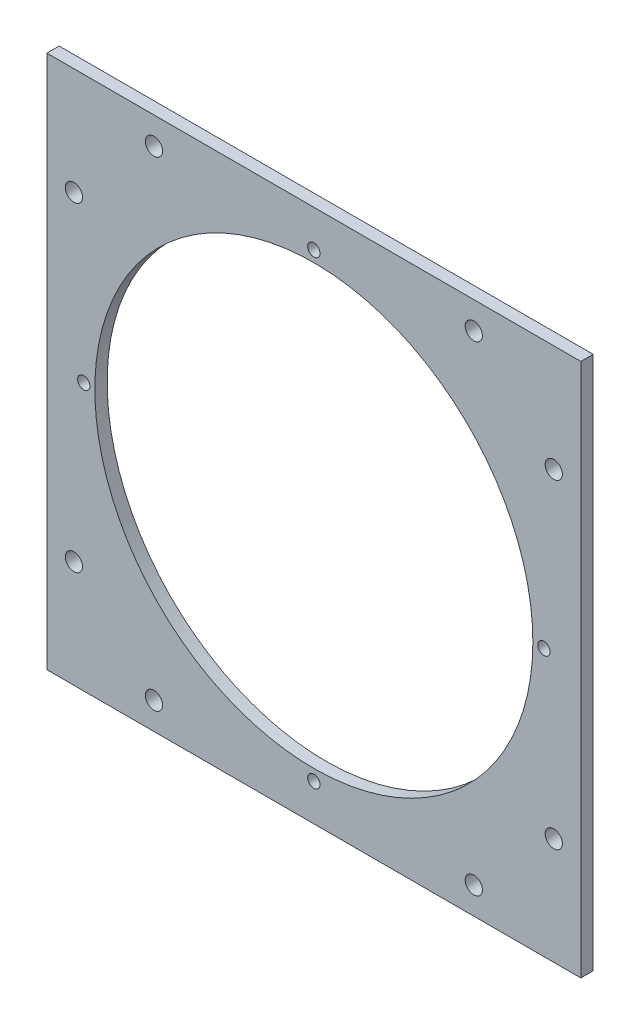
SolidWorks part; units mm, degrees
material "AISI 304"
ref_plane "Front Plane" through (0, 0, 0) normal (0, 0, 1) x (1, 0, 0)
ref_plane "Top Plane" through (0, 0, 0) normal (0, 1, 0) x (1, 0, 0)
ref_plane "Right Plane" through (0, 0, 0) normal (1, 0, 0) x (0, 0, -1)
sketch "Sketch2" plane through (0, 0, 0) normal (0, 0, 1) x (1, 0, 0)
  line L0 (0, 0) -> (0, 108.5) construction
  line L1 (-108.5, 108.5) -> (108.5, 108.5)
  line L2 (-108.5, 108.5) -> (-108.5, -108.5)
  line L3 (-108.5, -108.5) -> (108.5, -108.5)
  line L4 (108.5, 108.5) -> (108.5, -108.5)
  line L5 (-108.5, 108.5) -> (108.5, -108.5) construction
  line L6 (-108.5, -108.5) -> (108.5, 108.5) construction
  line L7 (0, 0) -> (108.5, 0) construction
  circle A0 centre (0, 0) radius 93.5 construction
  circle A1 centre (0, 0) radius 89
  circle A2 centre (0, 93.5) radius 2.75 construction
  circle A3 centre (93.5, 0) radius 2.75 construction
  circle A4 centre (0, -93.5) radius 2.75 construction
  circle A5 centre (-93.5, 0) radius 2.75 construction
  circle A6 centre (-97.5, -65) radius 3.5
  circle A7 centre (-97.5, 65) radius 3.5
  circle A8 centre (97.5, 65) radius 3.5
  circle A9 centre (97.5, -65) radius 3.5
  circle A10 centre (-65, -97.5) radius 3.5
  circle A11 centre (65, -97.5) radius 3.5
  circle A12 centre (65, 97.5) radius 3.5
  circle A13 centre (-65, 97.5) radius 3.5
  dimension "D1" = 187
  dimension "D2" = 178
  dimension "D4" = 5.5
  dimension "D5" = 5.5
  dimension "D6" = 5.5
  dimension "D7" = 5.5
  dimension "D8" = 7
  dimension "D9" = 97.5
  dimension "D12" = 97.5
  dimension "D3" = 217
  dimension "D10" = 65
  dimension "D11" = 130
  dimension "D13" = 130
  dimension "D14" = 65
extrude "Boss-Extrude1" add sketch "Sketch2" along normal blind 5
hole_wizard "M6 Tapped Hole1" positions "Sketch4" profile "Sketch3" tap size "M6" standard "ISO" end condition through all
sketch "Sketch4" plane through (0, 0, 0) normal (0, 0, -1) x (-1, 0, 0)
  point P0 (0, -93.5)
  dimension "D1" = 93.5
sketch "Sketch3" plane through (0, -93.5, 0) normal (1, 0, 0) x (0, 1, 0)
  line L0 (0, 0) -> (0, 5)
  line L1 (0, 5) -> (2.5, 5)
  line L2 (2.5, 5) -> (2.5, 0)
  line L5 (2.5, 0) -> (0, 0)
  line L11 (0, -6.35) -> (0, 107.95) construction
  dimension "Thru Tap Drill Dia." = 5
  dimension "Thru Tap Drill Depth" = 5
cosmetic thread "Hole Thread1" parameters "D2"=6
pattern_circular "CirPattern1" count 4 over 360 about axis through (0, 0, 0) along (0, 0, 1) of "M6 Tapped Hole1"
cosmetic thread "Hole Thread2" parameters "D2"=6
cosmetic thread "Hole Thread3" parameters "D2"=6
cosmetic thread "Hole Thread4" parameters "D2"=6
